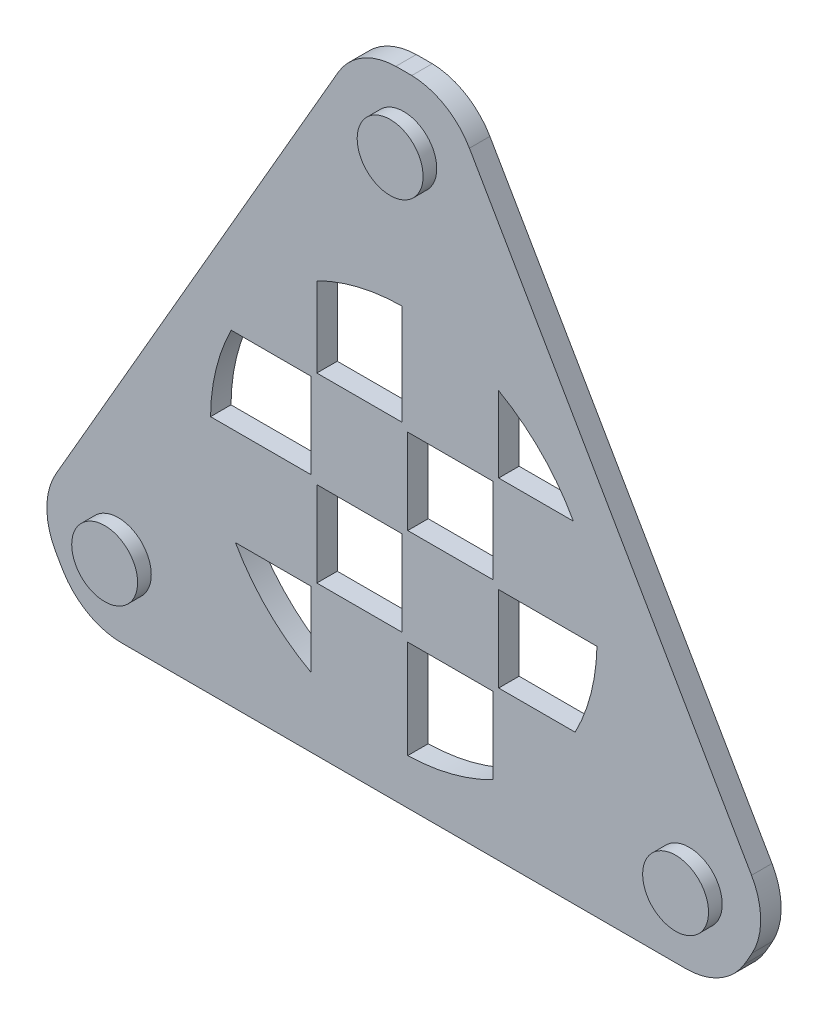
SolidWorks part; units mm, degrees
ref_plane "Спереди" through (0, 0, 0) normal (0, 0, 1) x (1, 0, 0)
ref_plane "Сверху" through (0, 0, 0) normal (0, 1, 0) x (1, 0, 0)
ref_plane "Справа" through (0, 0, 0) normal (1, 0, 0) x (0, 0, -1)
sketch "Sketch1" plane through (0, 0, 0) normal (0, 0, 1) x (1, 0, 0)
  line L0 (3.9, 6.755) -> (7.8, 0) construction
  line L2 (5.85, 10.1325) -> (11.7, 0) construction
  line L4 (7.8, 13.51) -> (15.6, 0) construction
  circle A61 centre (0, 0) radius 20
  circle A131 centre (0, 0) radius 1.25
  circle A484 centre (3.9, 0) radius 1.25
  circle A485 centre (7.8, 0) radius 1.25
  circle A486 centre (11.7, 0) radius 1.25
  circle A487 centre (15.6, 0) radius 1.25
  circle A488 centre (1.95, -3.3775) radius 1.25
  circle A489 centre (3.9, -6.755) radius 1.25
  circle A490 centre (5.85, -10.1325) radius 1.25
  circle A491 centre (7.8, -13.51) radius 1.25
  circle A492 centre (-1.95, -3.3775) radius 1.25
  circle A493 centre (-3.9, -6.755) radius 1.25
  circle A494 centre (-5.85, -10.1325) radius 1.25
  circle A495 centre (-7.8, -13.51) radius 1.25
  circle A496 centre (-3.9, 0) radius 1.25
  circle A497 centre (-7.8, 0) radius 1.25
  circle A498 centre (-11.7, 0) radius 1.25
  circle A499 centre (-15.6, 0) radius 1.25
  circle A500 centre (-1.95, 3.3775) radius 1.25
  circle A501 centre (-3.9, 6.755) radius 1.25
  circle A502 centre (-5.85, 10.1325) radius 1.25
  circle A503 centre (-7.8, 13.51) radius 1.25
  circle A504 centre (1.95, 3.3775) radius 1.25
  circle A505 centre (3.9, 6.755) radius 1.25
  circle A506 centre (5.85, 10.1325) radius 1.25
  circle A507 centre (7.8, 13.51) radius 1.25
  circle A508 centre (5.85, 3.3775) radius 1.25
  circle A509 centre (7.8, 6.755) radius 1.25
  circle A510 centre (9.75, 3.3775) radius 1.25
  circle A511 centre (11.7, 6.755) radius 1.25
  circle A512 centre (9.7491, 10.1341) radius 1.25
  circle A513 centre (13.6509, 3.3759) radius 1.25
  circle A514 centre (5.85, -3.3791) radius 1.25
  circle A515 centre (9.75, -3.3791) radius 1.25
  circle A516 centre (7.8, -6.7566) radius 1.25
  circle A517 centre (11.7, -6.7566) radius 1.25
  circle A518 centre (9.7491, -10.1356) radius 1.25
  circle A519 centre (13.6509, -3.3775) radius 1.25
  circle A520 centre (-0.0013, -6.7573) radius 1.25
  circle A521 centre (1.9487, -10.1348) radius 1.25
  circle A522 centre (-1.9513, -10.1348) radius 1.25
  circle A523 centre (-0.0013, -13.5123) radius 1.25
  circle A524 centre (-3.9032, -13.5123) radius 1.25
  circle A525 centre (3.9005, -13.5123) radius 1.25
  circle A526 centre (-5.8527, -3.3791) radius 1.25
  circle A527 centre (-7.8027, -6.7566) radius 1.25
  circle A528 centre (-9.7527, -3.3791) radius 1.25
  circle A529 centre (-11.7027, -6.7566) radius 1.25
  circle A530 centre (-13.6536, -3.3775) radius 1.25
  circle A531 centre (-9.7518, -10.1356) radius 1.25
  circle A532 centre (-5.8527, 3.3775) radius 1.25
  circle A533 centre (-9.7527, 3.3775) radius 1.25
  circle A534 centre (-7.8027, 6.755) radius 1.25
  circle A535 centre (-11.7027, 6.755) radius 1.25
  circle A536 centre (-9.7518, 10.1341) radius 1.25
  circle A537 centre (-13.6536, 3.3759) radius 1.25
  circle A538 centre (-0.0014, 6.7558) radius 1.25
  circle A539 centre (-1.9514, 10.1333) radius 1.25
  circle A540 centre (1.9486, 10.1333) radius 1.25
  circle A541 centre (-0.0014, 13.5108) radius 1.25
  circle A542 centre (3.9005, 13.5108) radius 1.25
  circle A543 centre (-3.9032, 13.5108) radius 1.25
  circle A544 centre (13.65, -1.1258) radius 2.2517 construction
  circle A545 centre (11.7009, -4.5044) radius 2.2522 construction
  circle A546 centre (9.75, -7.8834) radius 2.2522 construction
  circle A547 centre (7.7987, -11.2591) radius 2.2509 construction
  circle A548 centre (13.65, -1.1258) radius 0.65
  circle A549 centre (11.7009, -4.5044) radius 0.65
  circle A550 centre (9.75, -7.8834) radius 0.65
  circle A551 centre (7.7987, -11.2591) radius 0.65
  circle A552 centre (9.75, -1.1258) radius 0.65
  circle A553 centre (7.8009, -4.5044) radius 0.65
  circle A554 centre (5.85, -7.8834) radius 0.65
  circle A555 centre (3.8987, -11.2591) radius 0.65
  circle A556 centre (5.85, -1.1258) radius 0.65
  circle A557 centre (3.9009, -4.5044) radius 0.65
  circle A558 centre (1.95, -7.8834) radius 0.65
  circle A559 centre (-0.0013, -11.2591) radius 0.65
  circle A560 centre (1.95, -1.1258) radius 0.65
  circle A561 centre (0.0009, -4.5044) radius 0.65
  circle A562 centre (-1.95, -7.8834) radius 0.65
  circle A563 centre (-3.9013, -11.2591) radius 0.65
  circle A564 centre (-1.95, -1.1258) radius 0.65
  circle A565 centre (-3.8991, -4.5044) radius 0.65
  circle A566 centre (-5.85, -7.8834) radius 0.65
  circle A567 centre (-7.8013, -11.2591) radius 0.65
  circle A568 centre (-5.85, -1.1258) radius 0.65
  circle A569 centre (-7.7991, -4.5044) radius 0.65
  circle A570 centre (-9.75, -7.8834) radius 0.65
  circle A572 centre (-9.75, -1.1258) radius 0.65
  circle A573 centre (-11.6991, -4.5044) radius 0.65
  circle A576 centre (-13.65, -1.1258) radius 0.65
  circle A587 centre (0, 2.2517) radius 2.2517 construction
  circle A588 centre (0, 2.2517) radius 0.65
  circle A589 centre (3.9, 2.2517) radius 0.65
  circle A590 centre (7.8, 2.2517) radius 0.65
  circle A591 centre (11.7, 2.2517) radius 0.65
  circle A592 centre (15.6, 2.2517) radius 0.65
  circle A593 centre (1.9491, 5.6297) radius 2.2522 construction
  circle A594 centre (1.9491, 5.6297) radius 0.65
  circle A595 centre (5.8491, 5.6297) radius 0.65
  circle A596 centre (9.7491, 5.6297) radius 0.65
  circle A597 centre (13.6491, 5.6297) radius 0.65
  circle A598 centre (3.8991, 9.0072) radius 2.2522 construction
  circle A599 centre (3.8991, 9.0072) radius 0.65
  circle A600 centre (7.7991, 9.0072) radius 0.65
  circle A601 centre (11.6991, 9.0072) radius 0.65
  circle A602 centre (5.85, 12.3842) radius 2.2517 construction
  circle A603 centre (5.85, 12.3842) radius 0.65
  circle A604 centre (9.75, 12.3842) radius 0.65
  circle A605 centre (5.85, -14.6358) radius 0.65
  circle A606 centre (1.9509, -14.6353) radius 0.65
  circle A607 centre (-1.9491, -14.6353) radius 0.65
  circle A608 centre (-5.85, -14.6358) radius 0.65
  circle A609 centre (-15.6, 2.2517) radius 0.65
  circle A610 centre (-13.65, 5.6281) radius 0.65
  circle A611 centre (-11.7, 9.0056) radius 0.65
  circle A612 centre (-9.75, 12.3842) radius 0.65
  circle A613 centre (-5.85, 12.3842) radius 0.65
  circle A614 centre (-1.95, 12.3842) radius 0.65
  circle A615 centre (1.95, 12.3842) radius 0.65
  circle A616 centre (-7.8, 9.0056) radius 0.65
  circle A617 centre (-9.75, 5.6281) radius 0.65
  circle A618 centre (-11.7, 2.2517) radius 0.65
  circle A619 centre (-3.9, 9.0056) radius 0.65
  circle A620 centre (-5.85, 5.6281) radius 0.65
  circle A621 centre (-7.8, 2.2517) radius 0.65
  circle A622 centre (0, 9.0056) radius 0.65
  circle A623 centre (-1.95, 5.6281) radius 0.65
  circle A624 centre (-3.9, 2.2517) radius 0.65
  circle A625 centre (-15.5991, -4.5044) radius 0.65
  circle A626 centre (-13.65, -7.8834) radius 0.65
  circle A627 centre (-17.55, -7.8834) radius 0.65
  circle A628 centre (-19.5013, -11.2591) radius 0.65
  circle A629 centre (-15.6013, -11.2591) radius 0.65
  circle A630 centre (-11.7013, -11.2591) radius 0.65
  point P51 (0, 0)
  point P125 (-0.0013, -0.0008)
  point P231 (0, 0)
  dimension "D1" = 5
  dimension "D3" = 6
  dimension "D5" = 8
  dimension "D7" = 4
  dimension "D11" = 4
  dimension "D2" = 6
  dimension "D6" = 5
  dimension "D8" = 3
  dimension "D9" = 2
  dimension "D4" = 1.3
  dimension "D10" = 3
ref_plane "Plane1" through (0, 0, 10) normal (0, 0, 1) x (1, 0, 0)
sketch "Sketch2" plane through (0, 0, 10) normal (0, 0, 1) x (1, 0, 0)
  line L0 (-7.65, -15.1815) -> (-7.65, -8.35)
  line L2 (0.35, -16.9964) -> (0.35, -8.35)
  line L4 (-0.15, -16.9993) -> (-0.15, -8.35)
  line L5 (0.1469, -16.9994) -> (0.0704, -8.15) construction
  line L8 (-8.15, -14.919) -> (-8.15, -8.35)
  line L15 (16.9993, 0.15) -> (8.35, 0.15)
  line L17 (16.9964, -0.35) -> (8.35, -0.35)
  line L22 (14.919, 8.15) -> (8.35, 8.15)
  line L24 (15.1815, 7.65) -> (8.35, 7.65)
  line L26 (15.079, -7.85) -> (8.35, -7.85)
  line L28 (14.808, -8.35) -> (8.35, -8.35)
  line L33 (7.85, -15.079) -> (7.85, -8.35)
  line L34 (8.35, -14.808) -> (8.35, -8.35)
  line L36 (7.85, -7.85) -> (7.85, -0.35)
  line L37 (8.35, -7.85) -> (8.35, -0.35)
  line L38 (7.85, -8.35) -> (0.35, -8.35)
  line L39 (7.85, -7.85) -> (0.35, -7.85)
  line L40 (-0.15, -8.35) -> (-7.65, -8.35)
  line L41 (-0.15, -7.85) -> (-7.65, -7.85)
  line L42 (-0.15, -7.85) -> (-0.15, -0.35)
  line L43 (-0.0704, -8.15) -> (-0.1469, -16.9994) construction
  line L44 (0.0678, -7.85) -> (0, 0) construction
  line L45 (0.35, -7.85) -> (0.35, -0.35)
  line L46 (-8.15, -7.85) -> (-15.079, -7.85)
  line L47 (-8.15, -7.85) -> (-8.15, -0.35)
  line L48 (-7.65, -7.85) -> (-7.65, -0.35)
  line L49 (-8.15, -8.35) -> (-14.808, -8.35)
  line L50 (0.003, -0.35) -> (-0.0013, -0.35)
  line L53 (0.0013, 0.15) -> (-0.0013, 0.15)
  line L54 (-0.15, 0.15) -> (-7.65, 0.15)
  line L55 (-0.15, -0.35) -> (-7.65, -0.35)
  line L56 (7.85, -0.35) -> (0.35, -0.35)
  line L59 (7.85, 0.15) -> (0.35, 0.15)
  line L60 (7.85, 0.15) -> (7.85, 7.65)
  line L61 (8.35, 0.15) -> (8.35, 7.65)
  line L62 (-8.15, -0.35) -> (-16.9964, -0.35)
  line L65 (-8.15, 0.15) -> (-16.9993, 0.15)
  line L66 (-8.15, 0.15) -> (-8.15, 7.65)
  line L67 (-7.65, 0.15) -> (-7.65, 7.65)
  line L68 (-0.15, 0.15) -> (-0.15, 7.65)
  line L70 (0, 0) -> (-0.0678, -7.85) construction
  line L71 (0.35, 0.15) -> (0.35, 7.65)
  line L72 (7.85, 8.15) -> (7.85, 15.079)
  line L73 (8.35, 8.15) -> (8.35, 14.808)
  line L74 (7.85, 7.65) -> (0.35, 7.65)
  line L75 (7.85, 8.15) -> (0.35, 8.15)
  line L76 (-0.15, 8.15) -> (-0.15, 16.9993)
  line L79 (0.35, 8.15) -> (0.35, 16.9964)
  line L80 (-0.15, 7.65) -> (-7.65, 7.65)
  line L81 (-0.15, 8.15) -> (-7.65, 8.15)
  line L82 (-8.15, 8.15) -> (-8.15, 14.919)
  line L83 (-7.65, 8.15) -> (-7.65, 15.1815)
  line L84 (-8.15, 7.65) -> (-15.1815, 7.65)
  line L85 (-8.15, 8.15) -> (-14.919, 8.15)
  circle A52 centre (0, 0) radius 17
  circle A53 centre (0, 0) radius 18
  dimension "D1" = 36
  dimension "D4" = 2
  dimension "D2" = 2
  dimension "D5" = 2
  dimension "D6" = 8
  dimension "D7" = 0.5
  dimension "D8" = 8
  dimension "D9" = 8
  dimension "D3" = 8
  dimension "D10" = 0.5
  dimension "D11" = 0.5
extrude "Boss-Extrude1" add sketch "Sketch2" against normal blind 1.8
sketch "Sketch18" plane through (0, 0, 8.2) normal (0, 0, 1) x (1, 0, 0)
  line L0 (-7.85, -15.079) -> (-7.85, -8.15)
  line L2 (0.15, -16.9993) -> (0.15, -8.15)
  line L4 (-0.15, -16.9993) -> (-0.15, -8.15)
  line L5 (0.1469, -16.9994) -> (0.0704, -8.15) construction
  line L8 (-8.15, -14.919) -> (-8.15, -8.15)
  line L15 (16.9993, 0.15) -> (8.15, 0.15)
  line L17 (16.9993, -0.15) -> (8.15, -0.15)
  line L22 (14.919, 8.15) -> (8.15, 8.15)
  line L24 (15.079, 7.85) -> (8.15, 7.85)
  line L26 (15.079, -7.85) -> (8.15, -7.85)
  line L28 (14.919, -8.15) -> (8.15, -8.15)
  line L33 (7.85, -15.079) -> (7.85, -8.15)
  line L34 (8.15, -14.919) -> (8.15, -8.15)
  line L36 (7.85, -7.85) -> (7.85, -0.15)
  line L37 (8.15, -7.85) -> (8.15, -0.15)
  line L38 (7.85, -8.15) -> (0.15, -8.15)
  line L39 (7.85, -7.85) -> (0.15, -7.85)
  line L40 (-0.15, -8.15) -> (-7.85, -8.15)
  line L41 (-0.15, -7.85) -> (-7.85, -7.85)
  line L42 (-0.15, -7.85) -> (-0.15, -0.15)
  line L43 (-0.0704, -8.15) -> (-0.1469, -16.9994) construction
  line L44 (0.0678, -7.85) -> (0, 0) construction
  line L45 (0.15, -7.85) -> (0.15, -0.15)
  line L46 (-8.15, -7.85) -> (-15.079, -7.85)
  line L47 (-8.15, -7.85) -> (-8.15, -0.15)
  line L48 (-7.85, -7.85) -> (-7.85, -0.15)
  line L49 (-8.15, -8.15) -> (-14.919, -8.15)
  line L50 (0.0013, -0.15) -> (-0.0013, -0.15)
  line L53 (0.0013, 0.15) -> (-0.0013, 0.15)
  line L54 (-0.15, 0.15) -> (-7.85, 0.15)
  line L55 (-0.15, -0.15) -> (-7.85, -0.15)
  line L56 (7.85, -0.15) -> (0.15, -0.15)
  line L59 (7.85, 0.15) -> (0.15, 0.15)
  line L60 (7.85, 0.15) -> (7.85, 7.85)
  line L61 (8.15, 0.15) -> (8.15, 7.85)
  line L62 (-8.15, -0.15) -> (-16.9993, -0.15)
  line L65 (-8.15, 0.15) -> (-16.9993, 0.15)
  line L66 (-8.15, 0.15) -> (-8.15, 7.85)
  line L67 (-7.85, 0.15) -> (-7.85, 7.85)
  line L68 (-0.15, 0.15) -> (-0.15, 7.85)
  line L70 (0, 0) -> (-0.0678, -7.85) construction
  line L71 (0.15, 0.15) -> (0.15, 7.85)
  line L72 (7.85, 8.15) -> (7.85, 15.079)
  line L73 (8.15, 8.15) -> (8.15, 14.919)
  line L74 (7.85, 7.85) -> (0.15, 7.85)
  line L75 (7.85, 8.15) -> (0.15, 8.15)
  line L76 (-0.15, 8.15) -> (-0.15, 16.9993)
  line L79 (0.15, 8.15) -> (0.15, 16.9993)
  line L80 (-0.15, 7.85) -> (-7.85, 7.85)
  line L81 (-0.15, 8.15) -> (-7.85, 8.15)
  line L82 (-8.15, 8.15) -> (-8.15, 14.919)
  line L83 (-7.85, 8.15) -> (-7.85, 15.079)
  line L84 (-8.15, 7.85) -> (-15.079, 7.85)
  line L85 (-8.15, 8.15) -> (-14.919, 8.15)
  circle A52 centre (0, 0) radius 17
  circle A53 centre (0, 0) radius 18
  dimension "D1" = 36
  dimension "D4" = 2
  dimension "D2" = 2
  dimension "D5" = 2
  dimension "D6" = 8
  dimension "D8" = 8
  dimension "D9" = 8
  dimension "D3" = 8
extrude "Boss-Extrude10" add sketch "Sketch18" along normal blind 1.8 contours A52 L72 L75 L79 | A52 L15 L61 L24 | L80 L68 L54 L67 | L56 L36 L39 L45 | A52 L34 L28 | A52 L0 L40 L4 | A52 L62 L47 L46 | A52 L82 L85
sketch "Sketch3" plane through (0, 0, 8.2) normal (0, 0, -1) x (-1, 0, 0)
  circle A0 centre (0, 0) radius 17.6
  circle A1 centre (0, 0) radius 35
  circle M33 centre (0, 0) radius 18
extrude "Boss-Extrude2" add sketch "Sketch3" against normal blind 1.8 contours A1 M33
sketch "Sketch4" plane through (0, 0, 8.2) normal (0, 0, -1) x (-1, 0, 0)
  circle A0 centre (0, 0) radius 29 construction
  circle A1 centre (0, 29) radius 2.9
  circle A2 centre (25.1147, -14.5) radius 2.9
  circle A3 centre (-25.1147, -14.5) radius 2.9
  point P11 (0, 0)
  dimension "D1" = 3
extrude "Boss-Extrude3" add sketch "Sketch4" against normal blind 3
sketch "Sketch7" plane through (0, 0, 8.2) normal (0, 0, -1) x (-1, 0, 0)
  line L1 (0, 42) -> (-36.3731, -21)
  line L2 (-36.3731, -21) -> (36.3731, -21)
  line L3 (36.3731, -21) -> (0, 42)
  circle A2 centre (0, 0) radius 21 construction
  circle A3 centre (0, 0) radius 59.1314
extrude "Cut-Extrude1" cut sketch "Sketch7" against normal through all both and the other way through all
fillet "Fillet1" radius 6 6 edges at (-32.1865, -13.7487, 9.1) (-4.1865, 34.7487, 9.1) (28, -21, 9.1) (-28, -21, 9.1) (4.1865, 34.7487, 9.1) (32.1865, -13.7487, 9.1)
